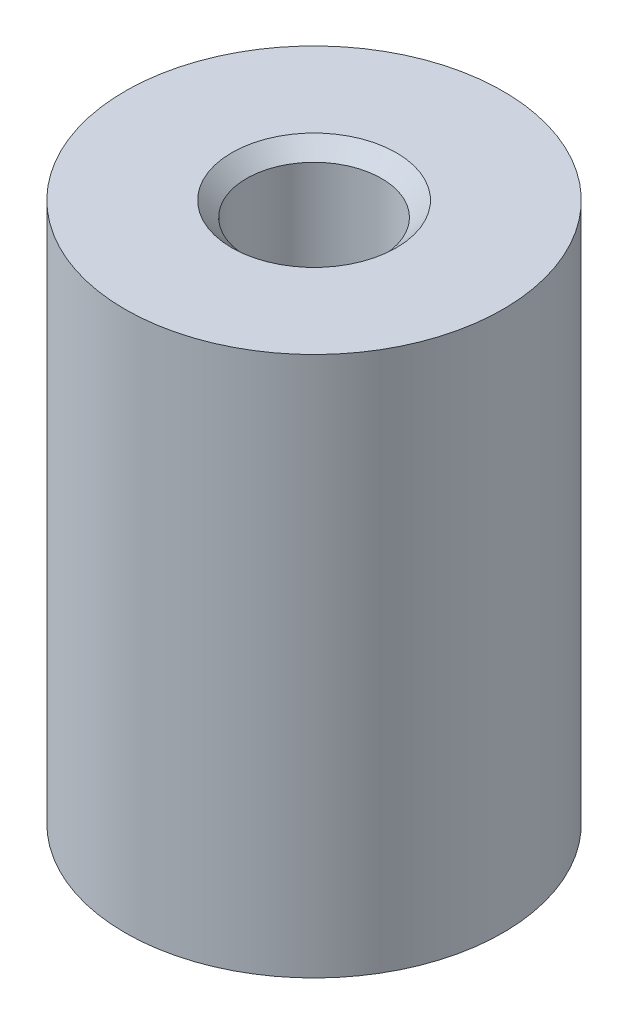
SolidWorks part; units mm, degrees
ref_plane "Ebene vorne" through (0, 0, 0) normal (0, 0, 1) x (1, 0, 0)
ref_plane "Ebene oben" through (0, 0, 0) normal (0, 1, 0) x (1, 0, 0)
ref_plane "Ebene rechts" through (0, 0, 0) normal (1, 0, 0) x (0, 0, -1)
sketch "Skizze1" plane through (0, 0, 0) normal (0, 1, 0) x (1, 0, 0)
  circle A0 centre (-1.8675, 0) radius 3.5
  dimension "D1" = 7
extrude "Aufsatz-Linear austragen1" add sketch "Skizze1" along normal blind 10
hole_wizard "M3 Gewindebohrung1" positions "Skizze2" profile "Skizze3" tap size "M3" standard "DIN" end condition through all
sketch "Skizze2" plane through (0, 10, 0) normal (0, 1, 0) x (1, 0, 0)
  circle A0 centre (-1.8675, 0) radius 3.5 construction
  point P0 (-1.8675, 0)
cosmetic thread "Bohrungsgewinde1" parameters "D2"=3
sketch "Skizze3" plane through (-1.8675, 10, 0) normal (1, 0, 0) x (0, 0, 1)
  line L0 (0, 0) -> (0, 10)
  line L1 (0, 10) -> (1.25, 10)
  line L2 (1.25, 10) -> (1.25, 0.275)
  line L3 (1.25, 0.275) -> (1.525, 0)
  line L5 (1.525, 0) -> (0, 0)
  line L6 (-1.25, 0.275) -> (-1.525, 0) construction
  line L11 (0, -6.35) -> (0, 107.95) construction
  dimension "Bohrerdurchmesser" = 2.5
  dimension "Bohrungstiefe" = 10
  dimension "Senkdurchmesser (Oben)" = 3.05
  dimension "Senkwinkel (Oben)" = 90
